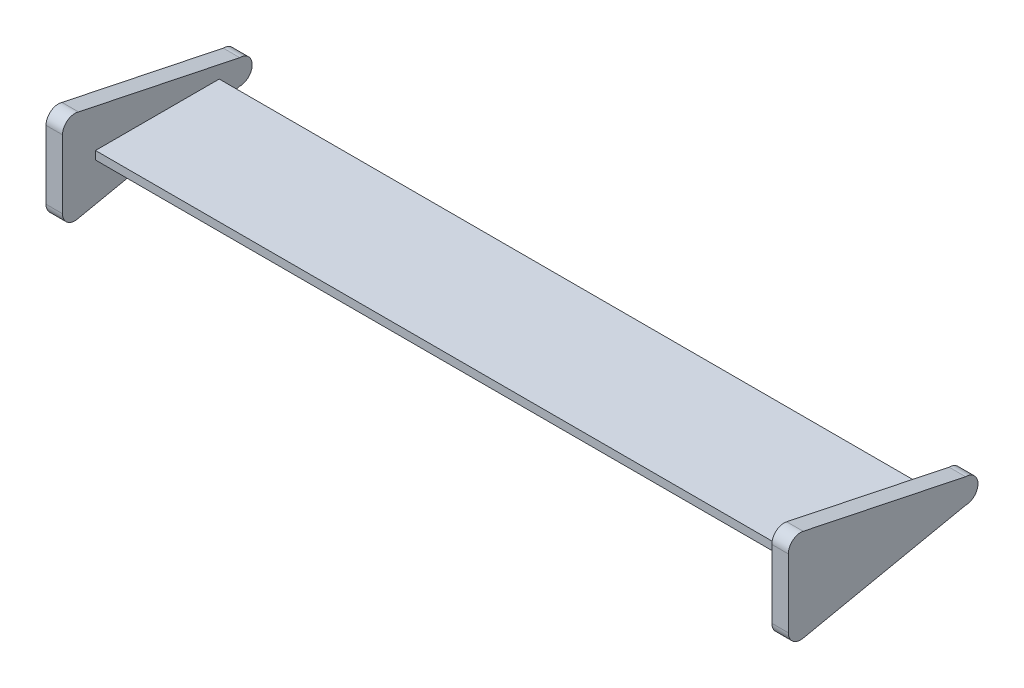
SolidWorks part; units mm, degrees
ref_plane "Front Plane" through (0, 0, 0) normal (0, 0, 1) x (1, 0, 0)
ref_plane "Top Plane" through (0, 0, 0) normal (0, 1, 0) x (1, 0, 0)
ref_plane "Right Plane" through (0, 0, 0) normal (1, 0, 0) x (0, 0, -1)
sketch "Sketch1" plane through (0, 0, 0) normal (0, 1, 0) x (1, 0, 0)
  line L1 (-45, 7.5) -> (45, 7.5)
  line L2 (-45, 7.5) -> (-45, -7.5)
  line L3 (-45, -7.5) -> (45, -7.5)
  line L4 (45, 7.5) -> (45, -7.5)
  line L5 (-45, 7.5) -> (45, -7.5) construction
  line L6 (-45, -7.5) -> (45, 7.5) construction
  point P0 (0, 0)
extrude "Boss-Extrude1" add sketch "Sketch1" along normal mid plane 1
sketch "Sketch2" plane through (45, 0, 0) normal (1, 0, 0) x (0, 0, -1)
  line L0 (-11.5, 4.1421) -> (-11.5, -4.1421)
  line L3 (-9.6935, 5.6105) -> (10, 1.5)
  line L4 (10, -1.5) -> (-9.6935, -5.6105)
  arc A0 (10, -1.5) -> (10, 1.5) centre (10, 0) ccw
  arc A1 (-9.6935, 5.6105) -> (-11.5, 4.1421) centre (-10, 4.1421) ccw
  arc A2 (-11.5, -4.1421) -> (-9.6935, -5.6105) centre (-10, -4.1421) ccw
extrude "Boss-Extrude2" add sketch "Sketch2" against normal blind 2
sketch "Sketch3" plane through (-45, 0, 0) normal (-1, 0, 0) x (0, 0, 1)
  line L0 (-10, 1.5) -> (9.5536, 5.5742)
  line L1 (-10, -1.5) -> (9.5536, -5.5742)
  line L2 (11.5, 4.1421) -> (11.5, -4.1421)
  arc A0 (-10, 1.5) -> (-10, -1.5) centre (-10, 0) ccw
  arc A1 (11.5, 4.1421) -> (9.5536, 5.5742) centre (10, 4.1421) ccw
  arc A2 (9.5536, -5.5742) -> (11.5, -4.1421) centre (10, -4.1421) ccw
extrude "Boss-Extrude3" add sketch "Sketch3" against normal blind 2
sketch "Sketch4" plane through (0, -0.5, 0) normal (0, -1, 0) x (1, 0, 0)
  line L1 (15, 1.5) -> (15, -1.5)
  line L2 (-15, 1.5) -> (-15, -1.5)
  line L3 (-15, -1.5) -> (-12, -1.5)
  line L4 (-12, -1.5) -> (-12, 1.5)
  line L5 (-12, 1.5) -> (-15, 1.5)
  line L6 (15, 1.5) -> (12, 1.5)
  line L7 (12, 1.5) -> (12, -1.5)
  line L8 (12, -1.5) -> (15, -1.5)
  point P4 (0, 0)
  point P8 (15, 0)
  point P11 (-15, 0)
extrude "Cut-Extrude1" cut sketch "Sketch4" against normal mid plane 0.5
